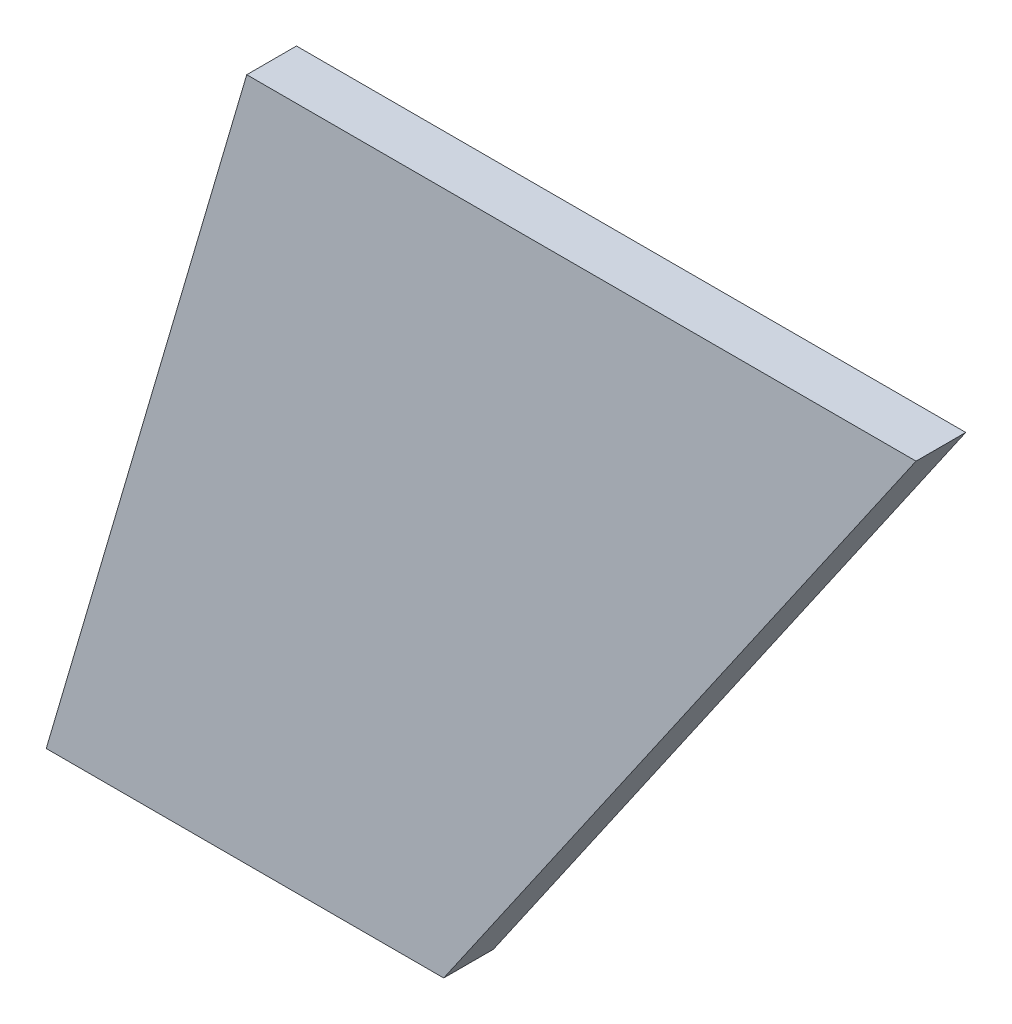
SolidWorks part; units mm, degrees
ref_plane "Front Plane" through (0, 0, 0) normal (0, 0, 1) x (1, 0, 0)
ref_plane "Top Plane" through (0, 0, 0) normal (0, 1, 0) x (1, 0, 0)
ref_plane "Right Plane" through (0, 0, 0) normal (1, 0, 0) x (0, 0, -1)
sketch "Sketch1" plane through (0, 0, 0) normal (0, 0, 1) x (1, 0, 0)
  line L0 (-107.3513, 48.7949) -> (-68.9359, 179.8005)
  line L1 (-68.9359, 179.8005) -> (59.2935, 179.8005)
  line L2 (59.2935, 179.8005) -> (-31.2021, 48.7949)
  line L3 (-31.2021, 48.7949) -> (-107.3513, 48.7949)
  point P2 (-91.3529, -37.924)
  point P5 (-15.5049, -132.2103)
  dimension "D1" = 128.2294
  dimension "D2" = 76.1492
  dimension "D3" = 73.657
  dimension "D4" = 131.0056
extrude "Boss-Extrude1" add sketch "Sketch1" against normal blind 9.525
